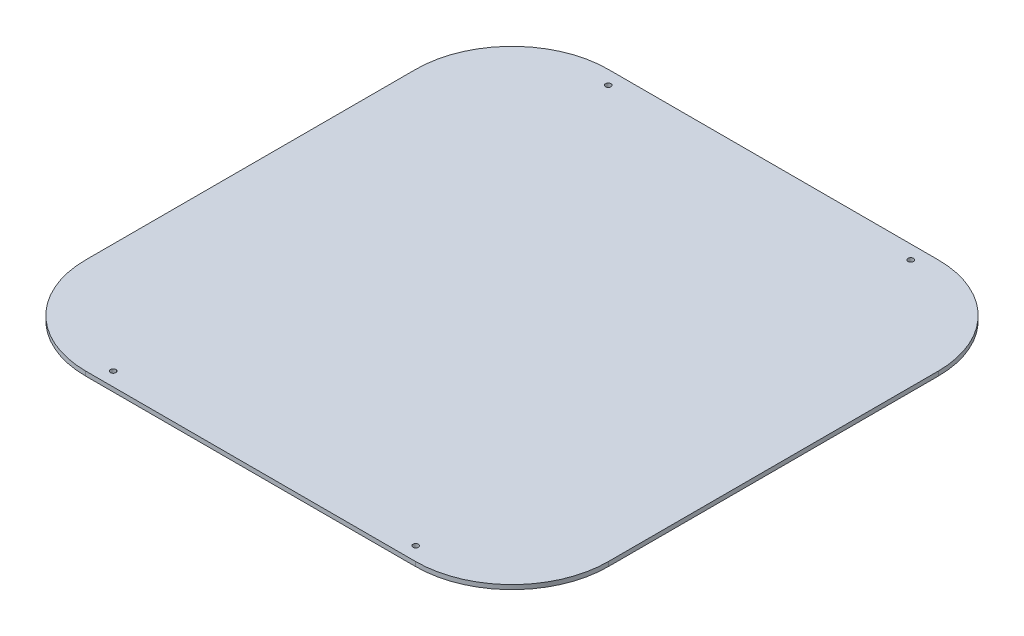
SolidWorks part; units mm, degrees
ref_plane "Plano frontal" through (0, 0, 0) normal (0, 0, 1) x (1, 0, 0)
ref_plane "Plano superior" through (0, 0, 0) normal (0, 1, 0) x (1, 0, 0)
ref_plane "Plano direito" through (0, 0, 0) normal (1, 0, 0) x (0, 0, -1)
sketch "Esboço1" plane through (0, 0, 0) normal (0, 1, 0) x (1, 0, 0)
  line L1 (-95, -95) -> (95, -95)
  line L2 (-95, -95) -> (-95, 95)
  line L3 (-95, 95) -> (95, 95)
  line L4 (95, -95) -> (95, 95)
  line L5 (-95, -95) -> (95, 95) construction
  line L6 (-95, 95) -> (95, -95) construction
  point P0 (0, 0)
  dimension "D1" = 190
  dimension "D2" = 190
extrude "Ressalto-extrusão1" add sketch "Esboço1" along normal blind 1.6
fillet "Filete1" radius 35 4 edges at (95, 0.8, -95) (95, 0.8, 95) (-95, 0.8, -95) (-95, 0.8, 95)
sketch "Esboço2" plane through (0, 1.6, 0) normal (0, 1, 0) x (1, 0, 0)
  line L2 (0, 95) -> (0, -95) construction
  line L4 (-95, 0) -> (95, 0) construction
  line L6 (-95, 60) -> (-95, -60) construction
  line L7 (95, -60) -> (95, 60) construction
  line L8 (-60, -95) -> (60, -95) construction
  line L9 (60, 95) -> (-60, 95) construction
  circle A0 centre (-55, 90) radius 1
  circle A1 centre (55, 90) radius 1
  circle A2 centre (55, -90) radius 1
  circle A3 centre (-55, -90) radius 1
  dimension "D1" = 2
  dimension "D2" = 110
  dimension "D3" = 180
extrude "Corte-extrusão1" cut sketch "Esboço2" against normal through all
